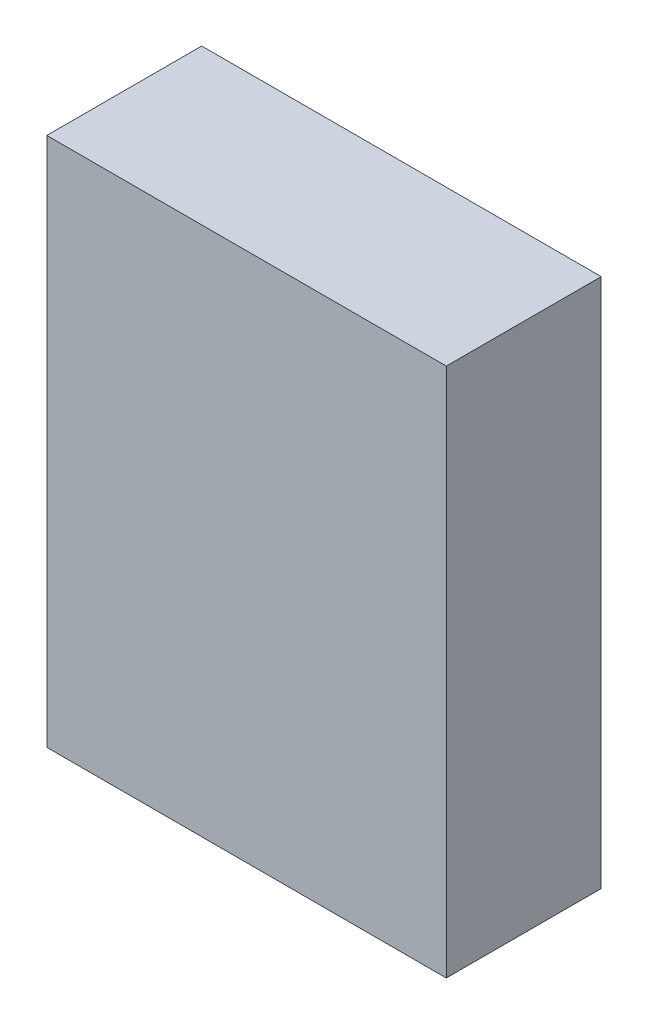
SolidWorks part; units mm, degrees
ref_plane "Front Plane" through (0, 0, 0) normal (0, 0, 1) x (1, 0, 0)
ref_plane "Top Plane" through (0, 0, 0) normal (0, 1, 0) x (1, 0, 0)
ref_plane "Right Plane" through (0, 0, 0) normal (1, 0, 0) x (0, 0, -1)
sketch "Sketch1" plane through (0, 0, 0) normal (0, 1, 0) x (1, 0, 0)
  line L1 (-49, 19) -> (49, 19)
  line L2 (-49, 19) -> (-49, -19)
  line L3 (-49, -19) -> (49, -19)
  line L4 (49, 19) -> (49, -19)
  point P4 (-49, 0)
  point P6 (0, 19)
  dimension "D1" = 38
  dimension "D2" = 98
extrude "Boss-Extrude1" add sketch "Sketch1" along normal blind 130
